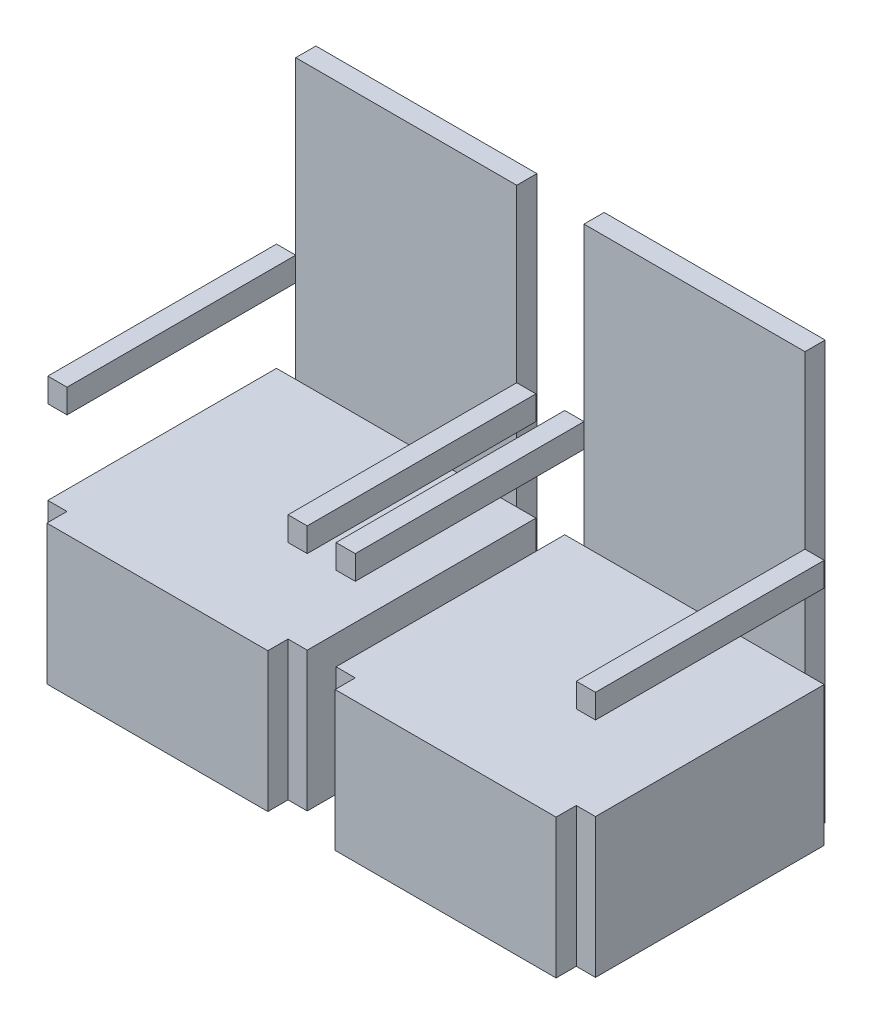
SolidWorks part; units mm, degrees
material "1023 Carbon Steel Sheet (SS)"
ref_plane "Front Plane" through (0, 0, 0) normal (0, 0, 1) x (1, 0, 0)
ref_plane "Top Plane" through (0, 0, 0) normal (0, 1, 0) x (1, 0, 0)
ref_plane "Right Plane" through (0, 0, 0) normal (1, 0, 0) x (0, 0, -1)
sketch "Sketch1" plane through (0, 0, 0) normal (0, 1, 0) x (1, 0, 0)
  line L0 (0, -55) -> (0, 55) construction
  line L13 (-723.9, 302.26) -> (-673.1, 302.26)
  line L14 (-673.1, 355.6) -> (-88.9, 355.6)
  line L15 (-723.9, 302.26) -> (-723.9, -302.26)
  line L16 (-673.1, -355.6) -> (-88.9, -355.6)
  line L17 (-88.9, 355.6) -> (-88.9, 302.26)
  line L18 (88.9, -355.6) -> (673.1, -355.6)
  line L19 (88.9, -355.6) -> (88.9, -302.26)
  line L20 (88.9, 355.6) -> (673.1, 355.6)
  line L21 (723.9, -302.26) -> (723.9, 302.26)
  line L22 (-673.1, 302.26) -> (-673.1, 355.6)
  line L23 (673.1, 302.26) -> (673.1, 355.6)
  line L24 (723.9, 302.26) -> (673.1, 302.26)
  line L25 (-55, 0) -> (55, 0) construction
  line L26 (673.1, -302.26) -> (673.1, -355.6)
  line L27 (-673.1, -302.26) -> (-673.1, -355.6)
  line L28 (-723.9, -302.26) -> (-673.1, -302.26)
  line L29 (723.9, -302.26) -> (673.1, -302.26)
  line L30 (-381, 355.6) -> (-381, -355.6) construction
  line L31 (381, -355.6) -> (381, 355.6) construction
  line L32 (-38.1, -302.26) -> (-88.9, -302.26)
  line L33 (-38.1, 302.26) -> (-38.1, -302.26)
  line L34 (-38.1, 302.26) -> (-88.9, 302.26)
  line L35 (38.1, -302.26) -> (88.9, -302.26)
  line L36 (38.1, -302.26) -> (38.1, 302.26)
  line L37 (38.1, 302.26) -> (88.9, 302.26)
  line L38 (-88.9, -302.26) -> (-88.9, -355.6)
  line L39 (88.9, 302.26) -> (88.9, 355.6)
  dimension "D1" = 1447.8
  dimension "D2" = 584.2
  dimension "D3" = 50.8
  dimension "D4" = 53.34
  dimension "D5" = 711.2
  dimension "D6" = 584.2
extrude "Boss-Extrude1" add sketch "Sketch1" along normal blind 368.3
sketch "Sketch2" plane through (0, 368.3, 0) normal (0, 1, 0) x (1, 0, 0)
  line L0 (0, -55) -> (0, 55) construction
  line L1 (-673.1, 302.26) -> (-88.9, 302.26)
  line L2 (-673.1, 302.26) -> (-673.1, 355.6)
  line L3 (-673.1, 355.6) -> (-88.9, 355.6)
  line L4 (-88.9, 302.26) -> (-88.9, 355.6)
  line L5 (673.1, 355.6) -> (88.9, 355.6)
  line L6 (88.9, 302.26) -> (88.9, 355.6)
  line L7 (673.1, 302.26) -> (88.9, 302.26)
  line L8 (673.1, 302.26) -> (673.1, 355.6)
extrude "Boss-Extrude2" add sketch "Sketch2" along normal blind 736.6
sketch "Sketch3" plane through (0, 0, -302.26) normal (0, 0, 1) x (1, 0, 0)
  line L0 (-673.1, 1104.9) -> (-673.1, 368.3) construction
  line L1 (-673.1, 589.28) -> (-723.9, 589.28)
  line L2 (-673.1, 589.28) -> (-673.1, 652.78)
  line L3 (-673.1, 652.78) -> (-723.9, 652.78)
  line L4 (-723.9, 589.28) -> (-723.9, 652.78)
  line L5 (-723.9, 368.3) -> (-673.1, 368.3) construction
  line L6 (0, -391.16) -> (0, 391.16) construction
  line L7 (673.1, 652.78) -> (723.9, 652.78)
  line L8 (723.9, 589.28) -> (723.9, 652.78)
  line L9 (673.1, 589.28) -> (723.9, 589.28)
  line L10 (673.1, 589.28) -> (673.1, 652.78)
  line L11 (-88.9, 1104.9) -> (-88.9, 368.3) construction
  line L12 (-88.9, 589.28) -> (-38.1, 589.28)
  line L13 (-88.9, 589.28) -> (-88.9, 652.78)
  line L14 (-88.9, 652.78) -> (-38.1, 652.78)
  line L15 (88.9, 589.28) -> (88.9, 652.78)
  line L16 (88.9, 1104.9) -> (88.9, 368.3) construction
  line L17 (-38.1, 368.3) -> (-38.1, 0) construction
  line L19 (38.1, 589.28) -> (38.1, 652.78)
  line L21 (-38.1, 589.28) -> (-38.1, 652.78)
  line L22 (38.1, 368.3) -> (38.1, 0) construction
  line L23 (38.1, 652.78) -> (88.9, 652.78)
  line L24 (38.1, 589.28) -> (88.9, 589.28)
  dimension "D1" = 63.5
  dimension "D2" = 220.98
extrude "Boss-Extrude3" add sketch "Sketch3" along normal up to surface (604.52 mm away) separate body up to face at (-698.5, 184.15, 302.26)
